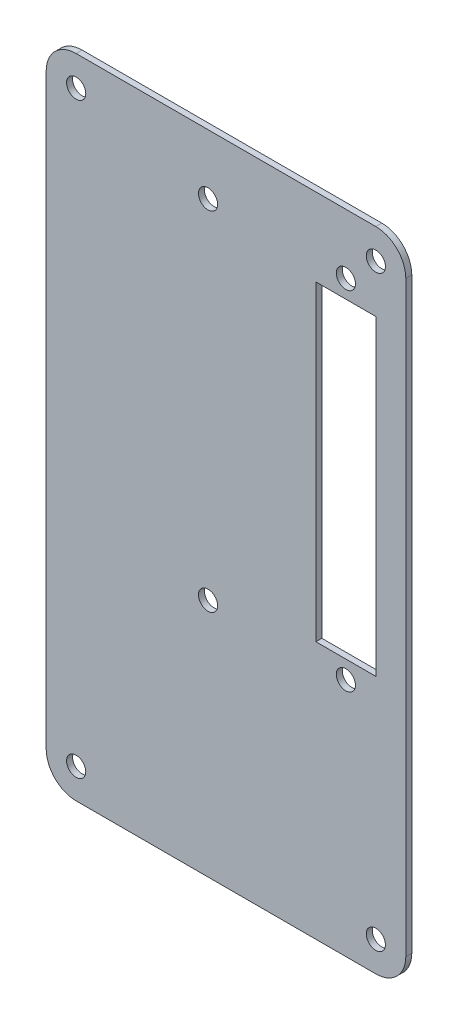
SolidWorks part; units mm, degrees
ref_plane "正面" through (0, 0, 0) normal (0, 0, 1) x (1, 0, 0)
ref_plane "平面" through (0, 0, 0) normal (0, 1, 0) x (1, 0, 0)
ref_plane "右側面" through (0, 0, 0) normal (1, 0, 0) x (0, 0, -1)
sketch "ｽｹｯﾁ1" plane through (0, 0, 0) normal (0, 0, 1) x (1, 0, 0)
  line L1 (-30, 54) -> (30, 54)
  line L2 (-30, 54) -> (-30, -54)
  line L3 (-30, -54) -> (30, -54)
  line L4 (30, 54) -> (30, -54)
  line L5 (-30, 54) -> (30, -54) construction
  line L6 (-30, -54) -> (30, 54) construction
  point P0 (0, 0)
  dimension "D1" = 108
  dimension "D2" = 60
extrude "ﾎﾞｽ - 押し出し1" add sketch "ｽｹｯﾁ1" along normal blind 1
sketch "ｽｹｯﾁ2" plane through (0, 0, 1) normal (0, 0, 1) x (1, 0, 0)
  line L0 (30, -54) -> (30, 54) construction
  line L1 (-3, 44) -> (20, 44) construction
  line L2 (-3, 44) -> (-3, -14) construction
  line L3 (-3, -14) -> (20, -14) construction
  line L4 (20, 44) -> (20, -14) construction
  line L5 (30, 54) -> (-30, 54) construction
  circle A0 centre (-3, 44) radius 1.6
  circle A1 centre (20, 44) radius 1.6
  circle A2 centre (-3, -14) radius 1.6
  circle A3 centre (20, -14) radius 1.6
  dimension "D5" = 3.2
  dimension "D6" = 3.2
  dimension "D7" = 3.2
  dimension "D8" = 3.2
  dimension "D1" = 58
  dimension "D2" = 23
  dimension "D3" = 10
  dimension "D4" = 10
extrude "ｶｯﾄ - 押し出し1" cut sketch "ｽｹｯﾁ2" against normal blind 5
sketch "ｽｹｯﾁ4" plane through (0, 0, 1) normal (0, 0, 1) x (1, 0, 0)
  line L0 (30, -54) -> (30, 54) construction
  line L1 (-25, -49) -> (25, -49) construction
  line L2 (-25, -49) -> (-25, 49) construction
  line L3 (-25, 49) -> (25, 49) construction
  line L4 (25, -49) -> (25, 49) construction
  line L5 (-25, -49) -> (25, 49) construction
  line L6 (-25, 49) -> (25, -49) construction
  line L8 (30, 54) -> (-30, 54) construction
  circle A0 centre (-25, 49) radius 1.6
  circle A1 centre (25, 49) radius 1.6
  circle A2 centre (-25, -49) radius 1.6
  circle A3 centre (25, -49) radius 1.6
  point P0 (0, 0)
  dimension "D3" = 3.2
  dimension "D4" = 3.2
  dimension "D5" = 3.2
  dimension "D6" = 3.2
  dimension "D1" = 5
  dimension "D2" = 5
extrude "ｶｯﾄ - 押し出し3" cut sketch "ｽｹｯﾁ4" against normal blind 5
fillet "ﾌｨﾚｯﾄ1" radius 5 4 edges at (30, -54, 0.5) (-30, -54, 0.5) (-30, 54, 0.5) (30, 54, 0.5)
sketch "ｽｹｯﾁ5" plane through (0, 0, 0) normal (0, 0, -1) x (-1, 0, 0)
  line L1 (-25, -11) -> (-15, -11)
  line L2 (-25, -11) -> (-25, 41)
  line L3 (-25, 41) -> (-15, 41)
  line L4 (-15, -11) -> (-15, 41)
  line L5 (-25, -11) -> (-15, 41) construction
  line L6 (-25, 41) -> (-15, -11) construction
  circle A0 centre (-20, 44) radius 1.6 construction
  circle A1 centre (-20, -14) radius 1.6 construction
  point P0 (-20, 15)
  dimension "D1" = 3
  dimension "D2" = 3
  dimension "D3" = 5
  dimension "D4" = 10
extrude "ｶｯﾄ - 押し出し4" cut sketch "ｽｹｯﾁ5" against normal through all
